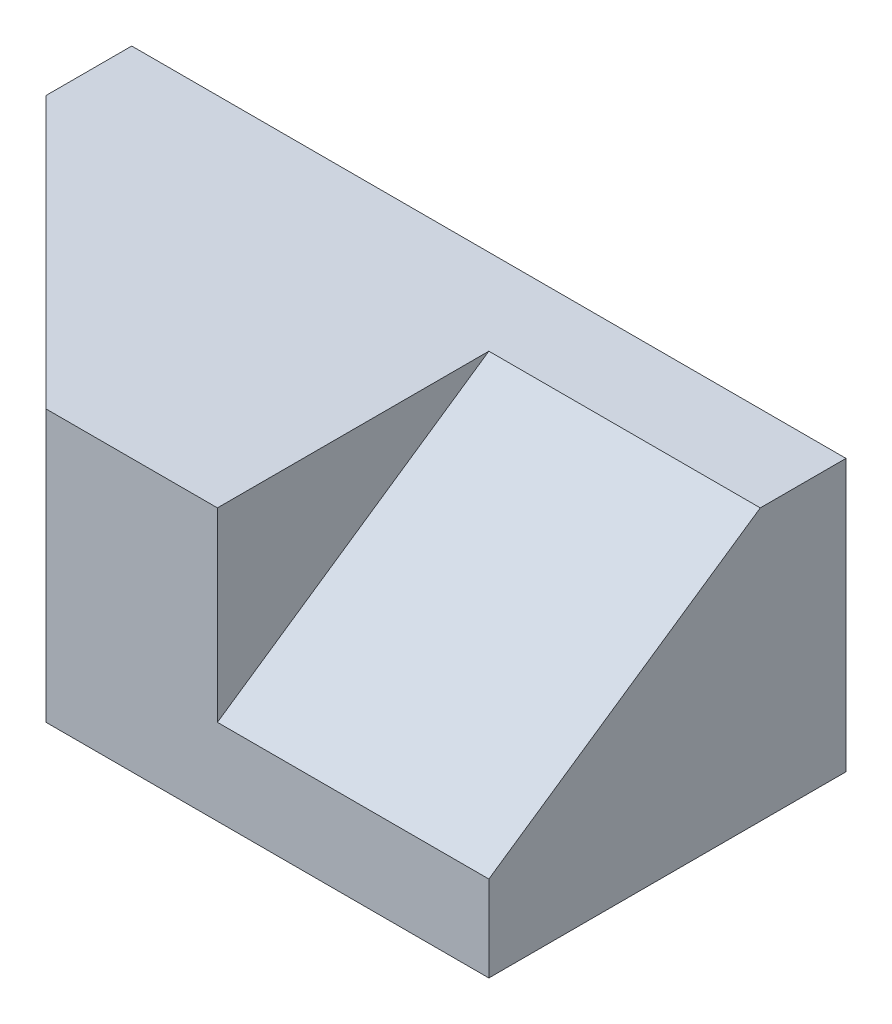
SolidWorks part; units mm, degrees
ref_plane "Front Plane" through (0, 0, 0) normal (0, 0, 1) x (1, 0, 0)
ref_plane "Top Plane" through (0, 0, 0) normal (0, 1, 0) x (1, 0, 0)
ref_plane "Right Plane" through (0, 0, 0) normal (1, 0, 0) x (0, 0, -1)
sketch "Sketch1" plane through (0, 0, 0) normal (0, 1, 0) x (1, 0, 0)
  line L0 (0, 0) -> (0, -12)
  line L1 (0, -12) -> (38, -50)
  line L2 (38, -50) -> (100, -50)
  line L3 (100, -50) -> (100, 0)
  line L4 (100, 0) -> (0, 0)
  dimension "D1" = 100
  dimension "D2" = 12
  dimension "D3" = 50
  dimension "D4" = 62
extrude "Boss-Extrude1" add sketch "Sketch1" along normal blind 38
sketch "Sketch2" plane through (100, 0, 0) normal (1, 0, 0) x (0, 0, -1)
  line L0 (-12, 38) -> (-50, 12)
  line L1 (-50, 38) -> (0, 38) construction
  line L2 (-50, 38) -> (-50, 0) construction
  line L3 (-50, 12) -> (-50, 38)
  line L4 (-50, 38) -> (-12, 38)
  line L5 (0, 38) -> (0, 0) construction
  line L6 (-50, 0) -> (0, 0) construction
  dimension "D1" = 12
  dimension "D2" = 12
extrude "Cut-Extrude1" cut sketch "Sketch2" against normal blind 38
